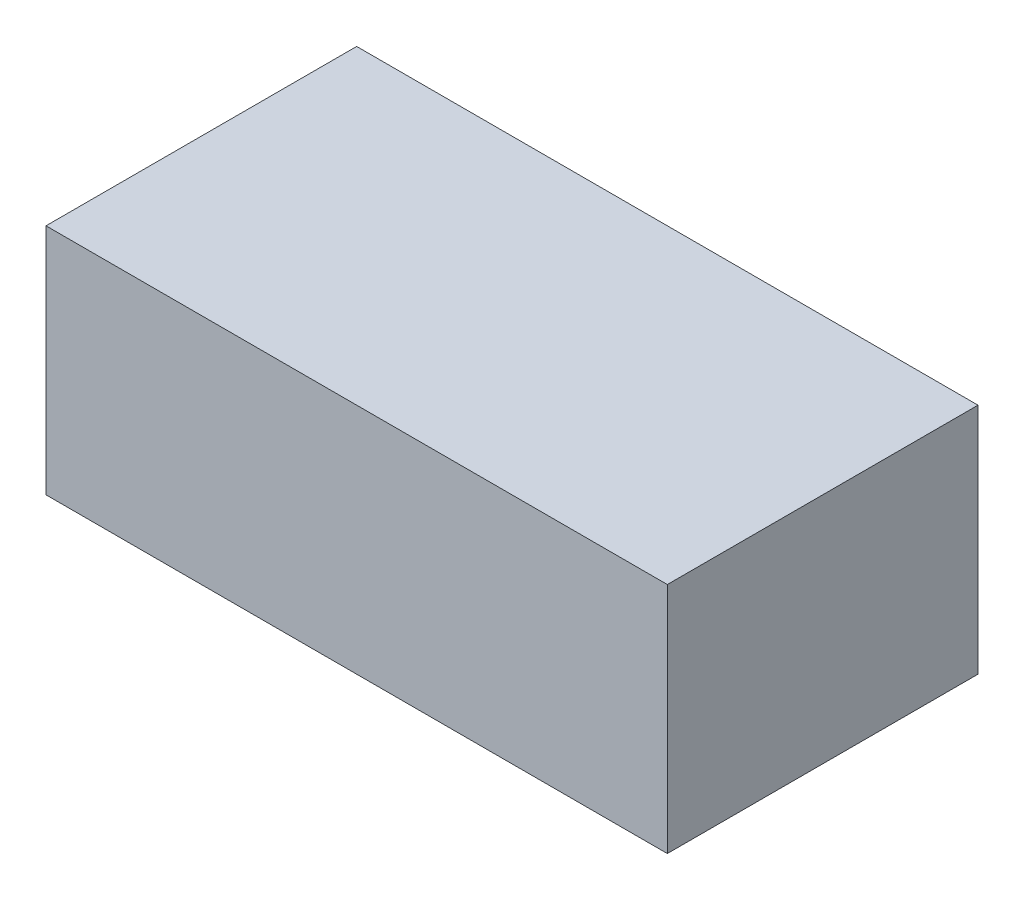
SolidWorks part; units mm, degrees
ref_plane "Front Plane" through (0, 0, 0) normal (0, 0, 1) x (1, 0, 0)
ref_plane "Top Plane" through (0, 0, 0) normal (0, 1, 0) x (1, 0, 0)
ref_plane "Right Plane" through (0, 0, 0) normal (1, 0, 0) x (0, 0, -1)
sketch "Sketch1" plane through (0, 0, 0) normal (0, 1, 0) x (1, 0, 0)
  line L1 (-25.4, 12.7) -> (25.4, 12.7)
  line L2 (-25.4, 12.7) -> (-25.4, -12.7)
  line L3 (-25.4, -12.7) -> (25.4, -12.7)
  line L4 (25.4, 12.7) -> (25.4, -12.7)
  line L5 (-25.4, 12.7) -> (25.4, -12.7) construction
  line L6 (-25.4, -12.7) -> (25.4, 12.7) construction
  point P0 (0, 0)
  dimension "D1" = 50.8
  dimension "D2" = 25.4
extrude "Boss-Extrude1" add sketch "Sketch1" along normal mid plane 19.05
